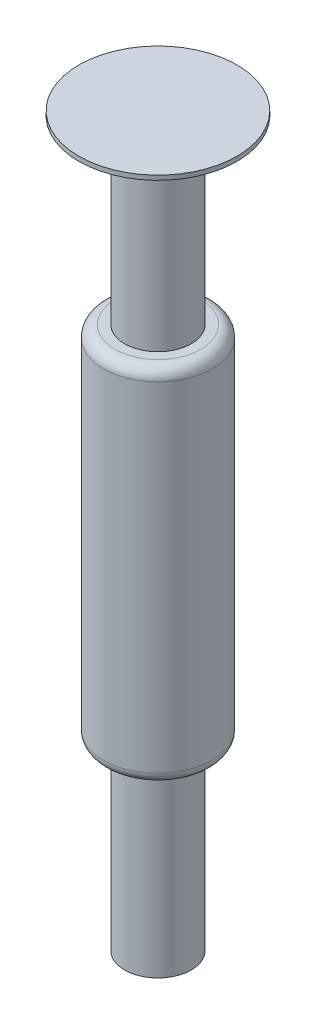
SolidWorks part; units mm, degrees
ref_plane "Front Plane" through (0, 0, 0) normal (0, 0, 1) x (1, 0, 0)
ref_plane "Top Plane" through (0, 0, 0) normal (0, 1, 0) x (1, 0, 0)
ref_plane "Right Plane" through (0, 0, 0) normal (1, 0, 0) x (0, 0, -1)
sketch "Sketch1" plane through (0, 0, 0) normal (0, 1, 0) x (1, 0, 0)
  circle A0 centre (0, 0) radius 4.8
extrude "Boss-Extrude2" add sketch "Sketch1" along normal blind 32
sketch "Sketch2" plane through (0, 32, 0) normal (0, 1, 0) x (1, 0, 0)
  circle A0 centre (0, 0) radius 2.95
extrude "Boss-Extrude3" add sketch "Sketch2" along normal blind 16
sketch "Sketch3" plane through (0, 0, 0) normal (0, -1, 0) x (1, 0, 0)
  circle A0 centre (0, 0) radius 2.95
extrude "Boss-Extrude4" add sketch "Sketch3" along normal blind 16
fillet "Fillet1" radius 1 2 edges at (0, 0, 4.8) (0, 32, 4.8)
sketch "Sketch4" plane through (0, 48, 0) normal (0, 1, 0) x (1, 0, 0)
  circle A0 centre (0, 0) radius 7
extrude "Boss-Extrude5" add sketch "Sketch4" along normal blind 0.4
